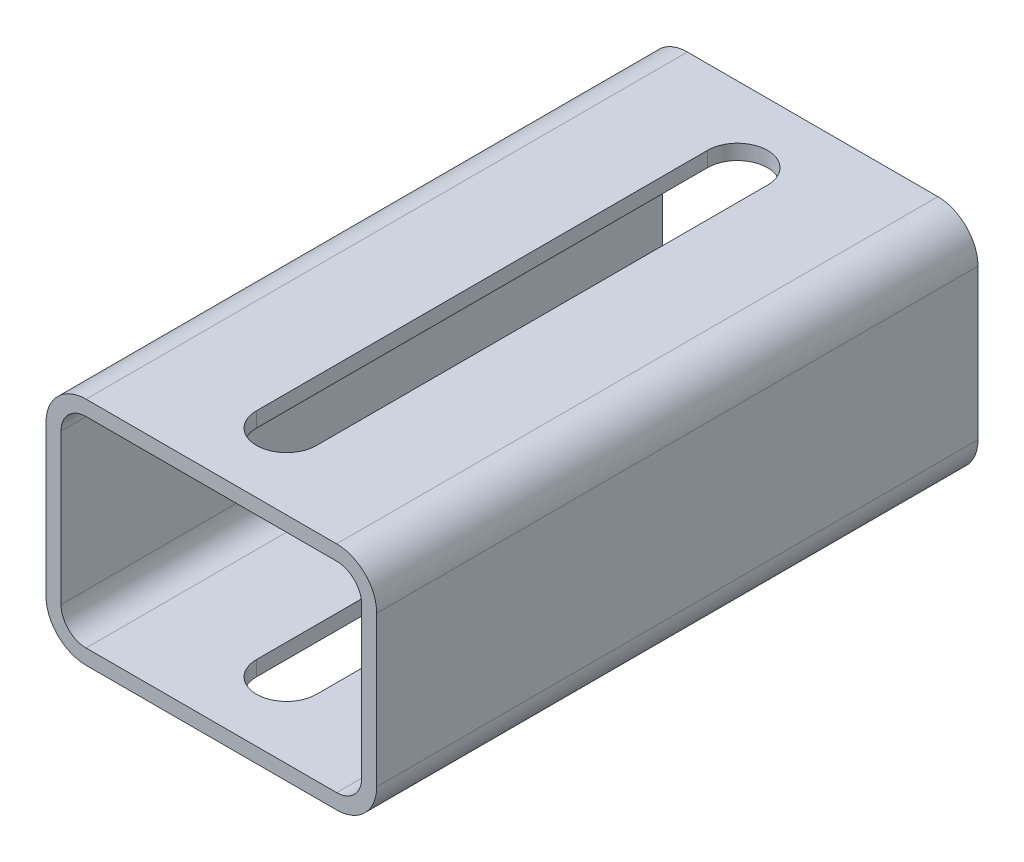
SolidWorks part; units mm, degrees
ref_plane "Front Plane" through (0, 0, 0) normal (0, 0, 1) x (1, 0, 0)
ref_plane "Top Plane" through (0, 0, 0) normal (0, 1, 0) x (1, 0, 0)
ref_plane "Right Plane" through (0, 0, 0) normal (1, 0, 0) x (0, 0, -1)
sketch "Sketch1" plane through (0, 0, 0) normal (0, 0, 1) x (1, 0, 0)
  line L1 (-25, 20) -> (25, 20)
  line L2 (-30, 15) -> (-30, -15)
  line L3 (-25, -20) -> (25, -20)
  line L4 (30, 15) -> (30, -15)
  line L5 (-30, 20) -> (30, -20) construction
  line L6 (-30, -20) -> (30, 20) construction
  arc A0 (25, 20) -> (30, 15) centre (25, 15) cw
  arc A1 (25, -20) -> (30, -15) centre (25, -15) ccw
  arc A2 (-30, -15) -> (-25, -20) centre (-25, -15) ccw
  arc A3 (-25, 20) -> (-30, 15) centre (-25, 15) ccw
  point P0 (0, 0)
  dimension "D3" = 5
  dimension "D1" = 60
  dimension "D2" = 40
extrude "Extrude-Thin1" add sketch "Sketch1" along normal mid plane 120 thin thin type one direction wall 3
sketch "Sketch2" plane through (0, 23, 0) normal (0, 1, 0) x (1, 0, 0)
  line L0 (0, 45) -> (0, -45) construction
  line L1 (6, 45) -> (6, -45)
  line L2 (-6, 45) -> (-6, -45)
  arc A0 (6, 45) -> (-6, 45) centre (0, 45) ccw
  arc A1 (-6, -45) -> (6, -45) centre (0, -45) ccw
  point P3 (0, 0)
  dimension "D2" = 6
  dimension "D1" = 90
extrude "Cut-Extrude1" cut sketch "Sketch2" against normal through all
